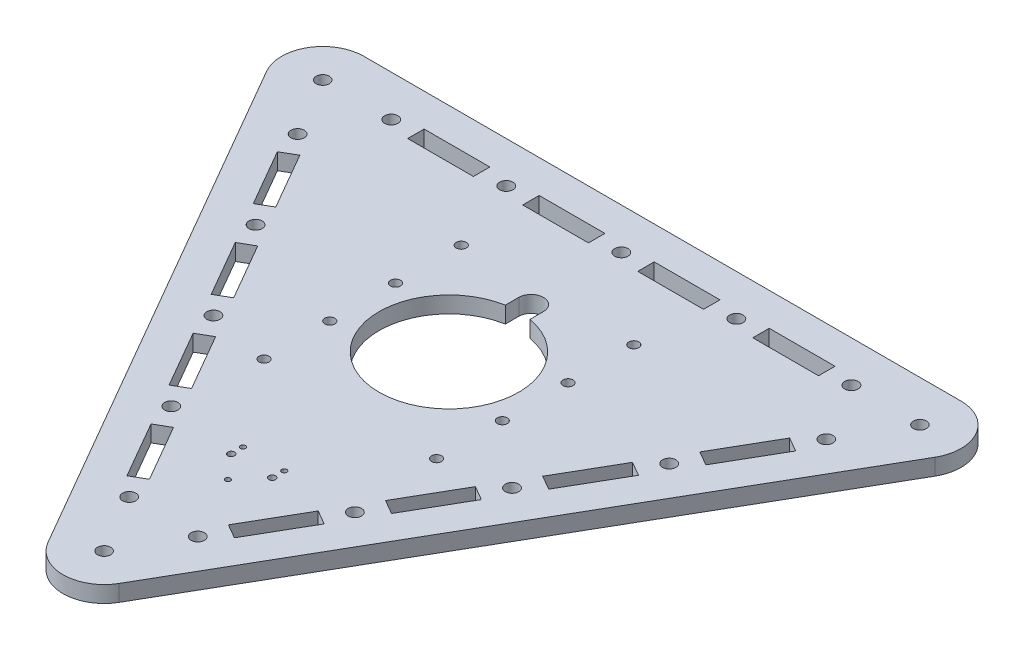
SolidWorks part; units mm, degrees
ref_plane "Front Plane" through (0, 0, 0) normal (0, 0, 1) x (1, 0, 0)
ref_plane "Top Plane" through (0, 0, 0) normal (0, 1, 0) x (1, 0, 0)
ref_plane "Right Plane" through (0, 0, 0) normal (1, 0, 0) x (0, 0, -1)
sketch "Sketch1" plane through (0, 0, 0) normal (0, 1, 0) x (1, 0, 0)
  line L1 (0, -259.8076) -> (225, 129.9038)
  line L2 (225, 129.9038) -> (-225, 129.9038)
  line L3 (-225, 129.9038) -> (0, -259.8076)
  circle A0 centre (0, 0) radius 129.9038 construction
  dimension "D1" = 450
extrude "Boss-Extrude1" add sketch "Sketch1" along normal blind 10
sketch "Axis" plane through (0, 0, 0) normal (0, 0, 1) x (1, 0, 0)
  line L0 (0, 0) -> (0, 10) construction
sketch "Sketch2" plane through (0, 10, 0) normal (0, 1, 0) x (1, 0, 0)
  line L1 (-52.5, 60) -> (-52.5, -60) construction
  circle A2 centre (-52.5, 60) radius 3.05
  circle A3 centre (-52.5, -60) radius 3.05
  circle A4 centre (-52.5, -20) radius 3.05
  circle A5 centre (-52.5, 20) radius 3.05
  dimension "D1" = 6.1
  dimension "D2" = 52.5
  dimension "D3" = 40
  dimension "D4" = 20
  dimension "D5" = 40
  dimension "D6" = 40
extrude "Cut-Extrude1" cut sketch "Sketch2" against normal through all
mirror "Mirror1" about plane through (0, 0, 0) normal (1, 0, 0) of "Cut-Extrude1"
fillet "Fillet1" radius 25 3 edges at (-225, 5, -129.9038) (225, 5, -129.9038) (0, 5, 259.8076)
sketch "Sketch3" plane through (0, 10, 0) normal (0, 1, 0) x (1, 0, 0)
  circle A0 centre (0, -209.8076) radius 4
  circle A1 centre (181.6987, 104.9038) radius 4
  circle A2 centre (-181.6987, 104.9038) radius 4
  dimension "D1" = 8
extrude "Cut-Extrude2" cut sketch "Sketch3" against normal through all
sketch "Sketch4" plane through (0, 10, 0) normal (0, 1, 0) x (1, 0, 0)
  line L0 (-181.6987, 104.9038) -> (181.6987, 104.9038) construction
  line L2 (15, 109.9038) -> (55, 109.9038)
  line L3 (15, 109.9038) -> (15, 99.9038)
  line L4 (15, 99.9038) -> (55, 99.9038)
  line L5 (55, 109.9038) -> (55, 99.9038)
  line L6 (15, 109.9038) -> (55, 99.9038) construction
  line L7 (15, 99.9038) -> (55, 109.9038) construction
  line L8 (-55, 109.9038) -> (-15, 109.9038)
  line L9 (-55, 109.9038) -> (-55, 99.9038)
  line L10 (-55, 99.9038) -> (-15, 99.9038)
  line L11 (-15, 109.9038) -> (-15, 99.9038)
  line L12 (-55, 109.9038) -> (-15, 99.9038) construction
  line L13 (-55, 99.9038) -> (-15, 109.9038) construction
  line L14 (-125, 109.9038) -> (-85, 109.9038)
  line L15 (-125, 109.9038) -> (-125, 99.9038)
  line L16 (-125, 99.9038) -> (-85, 99.9038)
  line L17 (-85, 109.9038) -> (-85, 99.9038)
  line L18 (-125, 109.9038) -> (-85, 99.9038) construction
  line L19 (-125, 99.9038) -> (-85, 109.9038) construction
  line L20 (85, 109.9038) -> (125, 109.9038)
  line L21 (85, 109.9038) -> (85, 99.9038)
  line L22 (85, 99.9038) -> (125, 99.9038)
  line L23 (125, 109.9038) -> (125, 99.9038)
  line L24 (85, 109.9038) -> (125, 99.9038) construction
  line L25 (85, 99.9038) -> (125, 109.9038) construction
  circle A0 centre (0, 104.9038) radius 4.05
  circle A1 centre (70, 104.9038) radius 4.05
  circle A3 centre (140, 104.9038) radius 4.05
  circle A4 centre (-140, 104.9038) radius 4.05
  circle A5 centre (-70, 104.9038) radius 4.05
  point P6 (35, 104.9038)
  point P11 (-35, 104.9038)
  point P24 (-105, 104.9038)
  point P29 (105, 104.9038)
  point P34 (-15, 104.9038)
  dimension "D1" = 8.1
  dimension "D2" = 40
  dimension "D3" = 10
  dimension "D4" = 30
  dimension "D5" = 15
  dimension "D6" = 30
  dimension "D7" = 30
  dimension "D8" = 15
  dimension "D9" = 15
  dimension "D10" = 15
  dimension "D11" = 15
extrude "Cut-Extrude3" cut sketch "Sketch4" against normal through all
pattern_circular "CirPattern1" count 3 over 360 about axis through (0, 0, 0) along (0, 1, 0) of "Cut-Extrude3"
sketch "Sketch7" plane through (0, 10, 0) normal (0, 1, 0) x (1, 0, 0)
  line L0 (0, 0) -> (0, -120) construction
  line L2 (0, -134.5) -> (12.5574, -112.75)
  line L3 (12.5574, -112.75) -> (-12.5574, -112.75)
  line L4 (-12.5574, -112.75) -> (0, -134.5)
  circle A0 centre (-12.5, -120) radius 2.05
  circle A1 centre (12.5, -120) radius 2.05
  circle A2 centre (0, -120) radius 7.25 construction
  circle A3 centre (-12.5574, -112.75) radius 1.55
  circle A4 centre (0, -134.5) radius 1.55
  circle A5 centre (12.5574, -112.75) radius 1.55
  dimension "D1" = 4.1
  dimension "D6" = 3.1
  dimension "D2" = 25
  dimension "D3" = 120
  dimension "D4" = 14.5
  dimension "D5" = 12.5
extrude "Cut-Extrude4" cut sketch "Sketch7" against normal through all contours A0 | A1 | A3 | A5 | A4
sketch "Sketch8" plane through (0, 10, 0) normal (0, 1, 0) x (1, 0, 0)
  line L0 (0, 35) -> (0, 50) construction
  line L5 (-7.5, 35) -> (-7.5, 50)
  line L6 (7.5, 35) -> (7.5, 50)
  circle A5 centre (0, 0) radius 42.5
  arc A6 (-7.5, 35) -> (7.5, 35) centre (0, 35) ccw
  arc A7 (7.5, 50) -> (-7.5, 50) centre (0, 50) ccw
  point P4 (0, 42.5)
  point P9 (0, 57.5)
  dimension "D1" = 85
  dimension "D2" = 15
  dimension "D3" = 15
extrude "Cut-Extrude5" cut sketch "Sketch8" against normal through all
equation "\"D5@Sketch4\"=\"D4@Sketch4\"/2"
equation "\"D6@Sketch4\"=\"D4@Sketch4\""
equation "\"D7@Sketch4\"=\"D4@Sketch4\""
equation "\"D8@Sketch4\"=\"D5@Sketch4\""
equation "\"D9@Sketch4\"=\"D5@Sketch4\""
equation "\"D10@Sketch4\"=\"D5@Sketch4\""
equation "\"D11@Sketch4\"=\"D5@Sketch4\""
equation "\"D4@Sketch2\"=\"D3@Sketch2\"/2"
equation "\"D5@Sketch2\"=\"D3@Sketch2\""
equation "\"D6@Sketch2\"=\"D3@Sketch2\""
equation "\"D5@Sketch7\"=\"D2@Sketch7\"/2"
